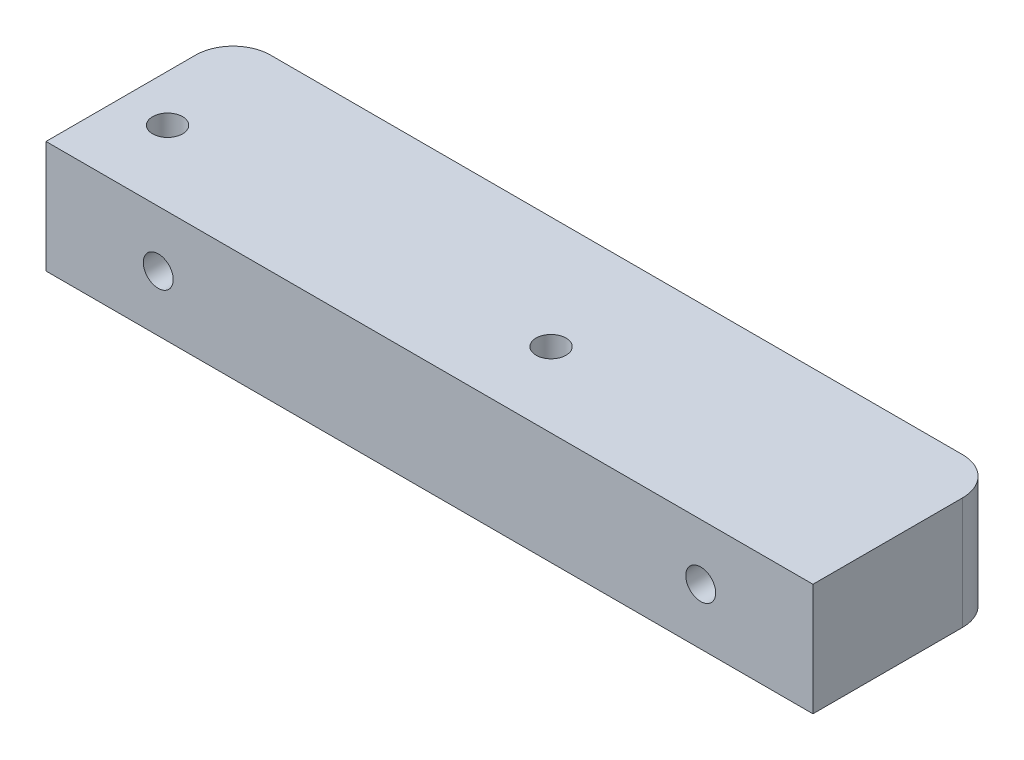
SolidWorks part; units mm, degrees
ref_plane "前视基准面" through (0, 0, 0) normal (0, 0, 1) x (1, 0, 0)
ref_plane "上视基准面" through (0, 0, 0) normal (0, 1, 0) x (1, 0, 0)
ref_plane "右视基准面" through (0, 0, 0) normal (1, 0, 0) x (0, 0, -1)
sketch "草图1" plane through (0, 0, 0) normal (0, 1, 0) x (1, 0, 0)
  line L1 (0, 0) -> (-41, 0)
  line L2 (0, 0) -> (0, 10)
  line L3 (0, 10) -> (-41, 10)
  line L4 (-41, 0) -> (-41, 10)
  dimension "D1" = 10
  dimension "D2" = 41
extrude "凸台-拉伸1" add sketch "草图1" along normal blind 6
sketch "草图2" plane through (0, 0, 0) normal (0, 0, 1) x (1, 0, 0)
  line L0 (0, 6) -> (0, 0) construction
  line L1 (-41, 6) -> (-41, 0) construction
  line L2 (-41, 0) -> (0, 0) construction
  circle A0 centre (-6, 3) radius 0.8
  circle A1 centre (-35, 3) radius 0.8
  dimension "D1" = 6
  dimension "D2" = 6
  dimension "D3" = 3
  dimension "D4" = 3
extrude "切除-拉伸1" cut sketch "草图2" against normal blind 6
fillet "圆角1" radius 2 2 edges at (-41, 3, -10) (0, 3, -10)
sketch "草图3" plane through (0, 0, 0) normal (0, -1, 0) x (-1, 0, 0)
  line L0 (41, 8) -> (41, 0) construction
  line L1 (2, 10) -> (39, 10) construction
  line L2 (0, 0) -> (0, 8) construction
  circle A0 centre (30.8, 7.5) radius 0.8
  circle A1 centre (10.2, 7.5) radius 0.8
  dimension "D1" = 10.2
  dimension "D3" = 10.2
  dimension "D2" = 2.5
  dimension "D4" = 2.5
extrude "切除-拉伸2" [suppressed] cut sketch "草图3" against normal blind 6
hole_wizard "打孔尺寸(%根据)内六角花形沉头螺钉的类型1" [suppressed] positions "草图4" profile "草图5" countersink size "M6" standard "GB"
sketch "草图4" [suppressed] plane through (0, 0, 0) normal (0, -1, 0) x (-1, 0, 0)
  point P0 (30.8, 7.5)
  point P3 (10.2, 7.5)
sketch "草图5" plane through (-30.8, 0, -7.5) normal (1, 0, 0) x (0, 0, -1)
  line L0 (0, 0) -> (0, 6)
  line L1 (0, 6) -> (0.8, 6)
  line L2 (0.8, 6) -> (0.8, 2.3)
  line L3 (0.8, 2.3) -> (3.1, 0)
  line L5 (3.1, 0) -> (0, 0)
  line L6 (-0.8, 2.3) -> (-3.1, 0) construction
  line L11 (0, -6.35) -> (0, 107.95) construction
  dimension "通孔孔直径" = 1.6
  dimension "通孔孔深度" = 6
  dimension "近端锥形沉头孔直径" = 6.2
  dimension "近端锥形沉头孔角度" = 90
chamfer "倒角1" [suppressed] distance 1 angle 45
sketch "草图6" plane through (0, 0, 0) normal (0, -1, 0) x (-1, 0, 0)
  line L0 (0, 0) -> (0, 8) construction
  line L1 (2, 10) -> (39, 10) construction
  line L2 (41, 8) -> (41, 0) construction
  circle A0 centre (38.5, 4) radius 0.8
  circle A1 centre (18, 4) radius 0.8
  dimension "D1" = 18
  dimension "D2" = 6
  dimension "D3" = 6
  dimension "D4" = 2.5
extrude "切除-拉伸3" cut sketch "草图6" against normal blind 10
